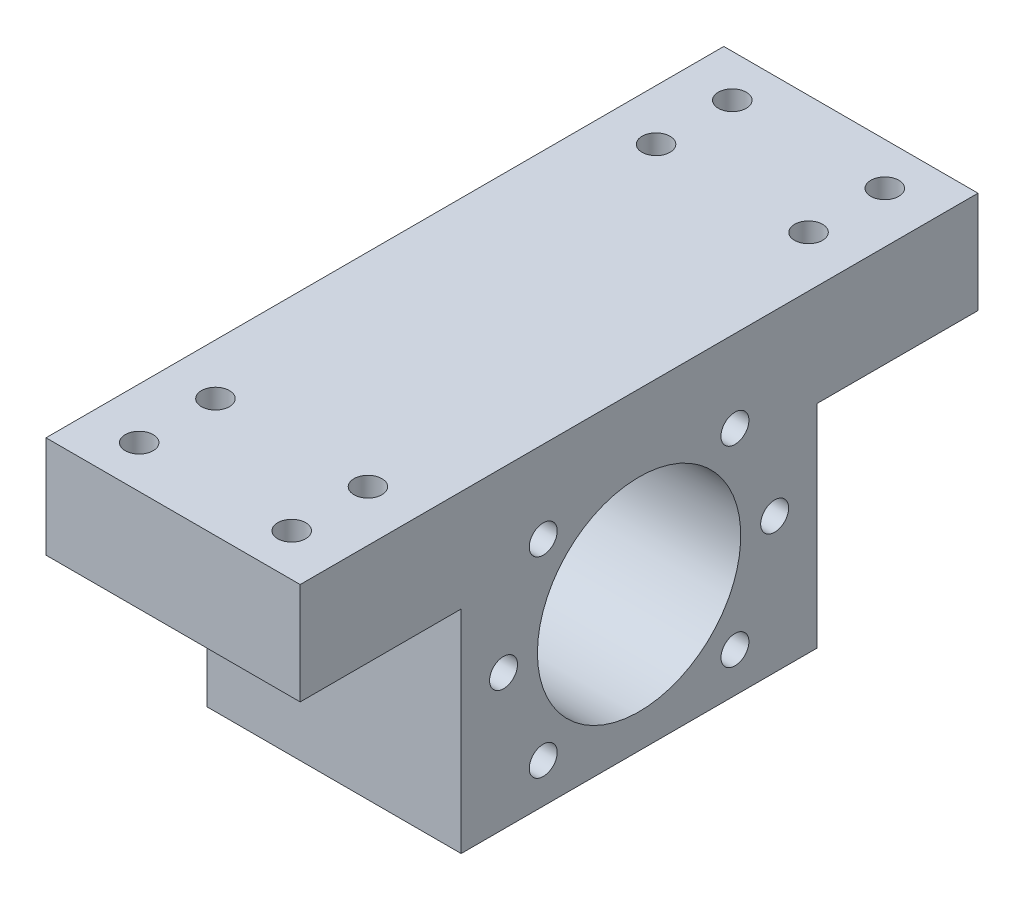
SolidWorks part; units mm, degrees
ref_plane "前视基准面" through (0, 0, 0) normal (0, 0, 1) x (1, 0, 0)
ref_plane "上视基准面" through (0, 0, 0) normal (0, 1, 0) x (1, 0, 0)
ref_plane "右视基准面" through (0, 0, 0) normal (1, 0, 0) x (0, 0, -1)
other "Configuration Table"
sketch "草图2" plane through (0, 0, 0) normal (1, 0, 0) x (0, 0, -1)
  line L1 (40, 41) -> (-40, 41)
  line L2 (40, 41) -> (40, -41)
  line L3 (40, -41) -> (-40, -41)
  line L4 (-40, 41) -> (-40, -41)
  line L5 (40, 41) -> (-40, -41) construction
  line L6 (40, -41) -> (-40, 41) construction
  point P0 (0, 0)
  dimension "D1" = 80
  dimension "D2" = 82
extrude "凸台-拉伸2" add sketch "草图2" along normal blind 30
sketch "草图3" plane through (0, 0, 0) normal (-1, 0, 0) x (0, 0, 1)
  line L0 (-40, 41) -> (40, 41) construction
  circle A0 centre (0, 20) radius 12
  dimension "D2" = 24
  dimension "D1" = 21
extrude "切除-拉伸1" cut sketch "草图3" against normal through all contours A0
sketch "草图7" plane through (30, 0, 0) normal (1, 0, 0) x (0, 0, -1)
  line L0 (-40, 29) -> (-21, 29)
  line L1 (-40, 41) -> (-40, -41) construction
  line L2 (-21, 29) -> (-21, 4)
  line L3 (-21, 4) -> (21, 4)
  line L4 (21, 4) -> (21, 29)
  line L5 (21, 29) -> (40, 29)
  line L6 (40, -41) -> (40, 41) construction
  line L7 (40, 29) -> (40, -41)
  line L8 (40, -41) -> (-40, -41)
  line L9 (-40, -41) -> (40, -41) construction
  line L10 (-40, -41) -> (-40, 29)
  dimension "D1" = 42
  dimension "D2" = 25
  dimension "D3" = 19
  dimension "D4" = 70
  dimension "D5" = 70
extrude "切除-拉伸2" cut sketch "草图7" against normal through all
sketch "草图8" plane through (0, 29, 0) normal (0, -1, 0) x (1, 0, 0)
  line L0 (0, 0) -> (56.5751, 0) construction
  line L1 (0, 40) -> (30, 40) construction
  line L2 (15, 40) -> (15, -41.1724) construction
  line L3 (0, 21) -> (30, 21) construction
  line L4 (0, 21) -> (0, 40) construction
  circle A0 centre (6, 26) radius 2
  circle A1 centre (24, 26) radius 2
  circle A4 centre (6, 35) radius 2
  circle A5 centre (24, 35) radius 2
  circle A6 centre (24, -35) radius 2
  circle A7 centre (24, -26) radius 2
  circle A8 centre (6, -26) radius 2
  circle A9 centre (6, -35) radius 2
  point P12 (6, 35)
  dimension "D2" = 4
  dimension "D7" = 4
  dimension "D5" = 5
  dimension "D6" = 6
  dimension "D8" = 5
sketch "草图4" plane through (30, 0, 0) normal (1, 0, 0) x (0, 0, -1)
  circle A0 centre (-11.3137, 8.6863) radius 2.25
  circle A1 centre (11.3137, 31.3137) radius 2.25
  circle A2 centre (-11.3137, 31.3137) radius 2.25
  circle A3 centre (-16, 20) radius 2.25
  circle A4 centre (11.3137, 8.6863) radius 2.25
  circle A5 centre (16, 20) radius 2.25
hole_wizard "M4 螺纹孔1" positions "草图11" profile "草图12" tap size "M4" standard "GB" end condition through all
sketch "草图11" plane through (0, 0, 0) normal (-1, 0, 0) x (0, 0, 1)
  point P0 (-11.3137, 31.3137)
  point P3 (11.3137, 8.6863)
  point P6 (11.3137, 31.3137)
  point P9 (16, 20)
  point P12 (-11.3137, 8.6863)
  point P15 (-16, 20)
sketch "草图12" plane through (0, 31.3137, -11.3137) normal (0, 1, 0) x (0, 0, 1)
  line L0 (0, 0) -> (0, 30)
  line L1 (0, 30) -> (1.65, 30)
  line L2 (1.65, 30) -> (1.65, 0)
  line L5 (1.65, 0) -> (0, 0)
  line L11 (0, -6.35) -> (0, 107.95) construction
  dimension "通孔螺纹孔钻头直径" = 3.3
  dimension "通孔螺纹孔钻头深度" = 30
cosmetic thread "孔螺蚊线1" parameters "D2"=4
cosmetic thread "孔螺蚊线2" parameters "D2"=4
cosmetic thread "孔螺蚊线3" parameters "D2"=4
cosmetic thread "孔螺蚊线4" parameters "D2"=4
cosmetic thread "孔螺蚊线5" parameters "D2"=4
cosmetic thread "孔螺蚊线6" parameters "D2"=4
hole_wizard "M4 螺纹孔2" positions "草图13" profile "草图14" tap size "M4" standard "GB" end condition through all
sketch "草图13" plane through (0, 29, 0) normal (0, -1, 0) x (-1, 0, 0)
  point P0 (-24, 35)
  point P3 (-6, 35)
  point P6 (-6, 26)
  point P9 (-24, 26)
  point P12 (-6, -35)
  point P15 (-6, -26)
  point P18 (-24, -26)
  point P21 (-24, -35)
sketch "草图14" plane through (24, 29, -35) normal (1, 0, 0) x (0, 0, -1)
  line L0 (0, 0) -> (0, 12)
  line L1 (0, 12) -> (1.65, 12)
  line L2 (1.65, 12) -> (1.65, 0)
  line L5 (1.65, 0) -> (0, 0)
  line L11 (0, -6.35) -> (0, 107.95) construction
  dimension "通孔螺纹孔钻头直径" = 3.3
  dimension "通孔螺纹孔钻头深度" = 12
cosmetic thread "孔螺蚊线7" parameters "D2"=4
cosmetic thread "孔螺蚊线8" parameters "D2"=4
cosmetic thread "孔螺蚊线9" parameters "D2"=4
cosmetic thread "孔螺蚊线10" parameters "D2"=4
cosmetic thread "孔螺蚊线11" parameters "D2"=4
cosmetic thread "孔螺蚊线12" parameters "D2"=4
cosmetic thread "孔螺蚊线13" parameters "D2"=4
cosmetic thread "孔螺蚊线14" parameters "D2"=4
